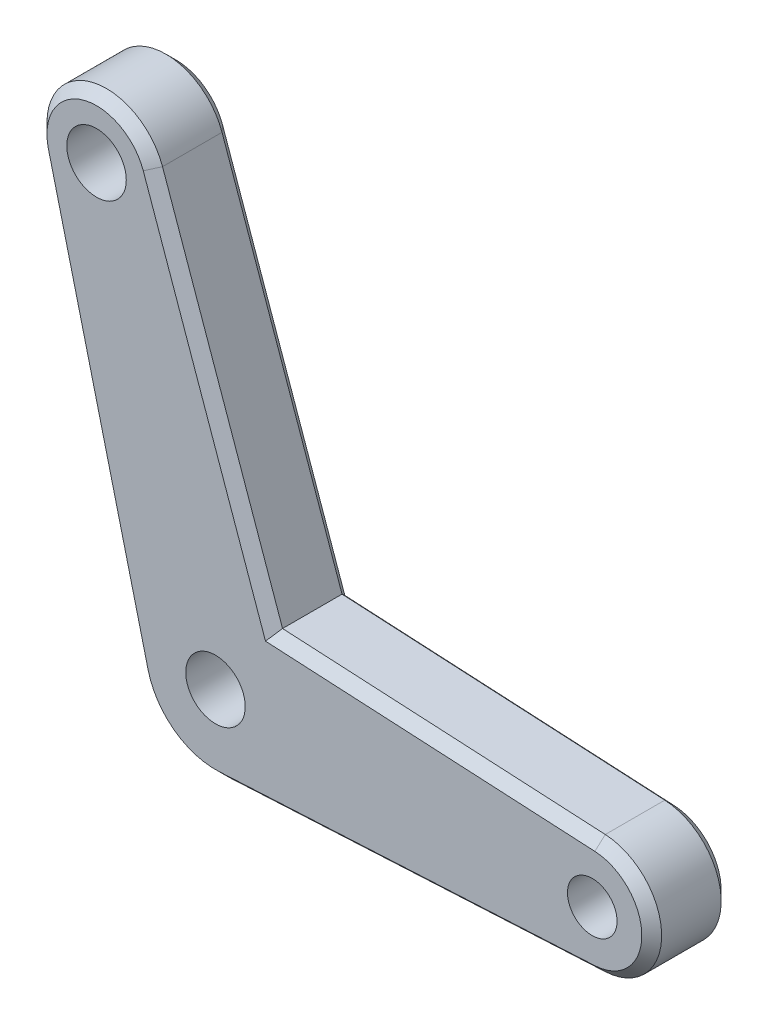
SolidWorks part; units mm, degrees
ref_plane "Alzado" through (0, 0, 0) normal (0, 0, 1) x (1, 0, 0)
ref_plane "Planta" through (0, 0, 0) normal (0, 1, 0) x (1, 0, 0)
ref_plane "Vista lateral" through (0, 0, 0) normal (1, 0, 0) x (0, 0, -1)
sketch "Croquis7" plane through (0, 0, 0) normal (0, 0, 1) x (1, 0, 0)
  circle A0 centre (0, 0) radius 3
  circle A1 centre (0, 0) radius 1.5
  dimension "D1" = 6
  dimension "D2" = 3
extrude "Saliente-Extruir4" add sketch "Croquis7" against normal blind 4
sketch "Croquis9" plane through (0, 0, 0) normal (0, 0, 1) x (1, 0, 0)
  line L0 (0, 0) -> (16185.8284, 0) construction
  line L1 (0, 0) -> (19, 0) construction
  line L2 (0.2105, 3.9945) -> (19.1579, 2.9958)
  line L3 (0.2105, -3.9945) -> (19.1579, -2.9958)
  circle A0 centre (0, 0) radius 1.5
  circle A1 centre (19, 0) radius 1.25
  arc A3 (19.1579, -2.9958) -> (19.1579, 2.9958) centre (19, 0) ccw
  arc A4 (0.2105, 3.9945) -> (0.2105, -3.9945) centre (0, 0) ccw
  point P5 (9.5, 0)
  dimension "D2" = 3
  dimension "D3" = 2.5
  dimension "D4" = 3
  dimension "D5" = 8
  dimension "D1" = 19
extrude "Saliente-Extruir5" add sketch "Croquis9" against normal blind 4
sketch "Croquis2" plane through (0, 0, -4) normal (0, 0, 1) x (1, 0, 0)
  line L6 (-3.1711, 20.9987) -> (3.7719, 1.3316)
  line L7 (-8.9115, 19.2766) -> (-3.882, -0.9646)
  circle A1 centre (0, 0) radius 3.02
  circle A2 centre (-6, 20) radius 1.5
  arc A3 (-3.1711, 20.9987) -> (-8.9115, 19.2766) centre (-6, 20) ccw
  arc A4 (-3.882, -0.9646) -> (3.7719, 1.3316) centre (0, 0) ccw
  dimension "D1" = 3
  dimension "D2" = 3
  dimension "D3" = 20
  dimension "D4" = 6
extrude "Saliente-Extruir2" add sketch "Croquis2" along normal through all
chamfer "Chaflán1" distance 0.5 angle 45 14 edges at (9.6842, -3.4951, 0) (9.6842, -3.4951, -4) (22, 0, 0) (22, 0, -4) (11.0197, 3.4248, -4) (11.0197, 3.4248, 0) (-6.3967, 9.156, -4) (-6.3967, 9.156, 0) (-6.862, 22.8735, -4) (-6.862, 22.8735, 0) (-0.1448, 12.4262, -4) (-0.1448, 12.4262, 0) (-2.3801, -3.2148, 0) (-2.3801, -3.2148, -4)
